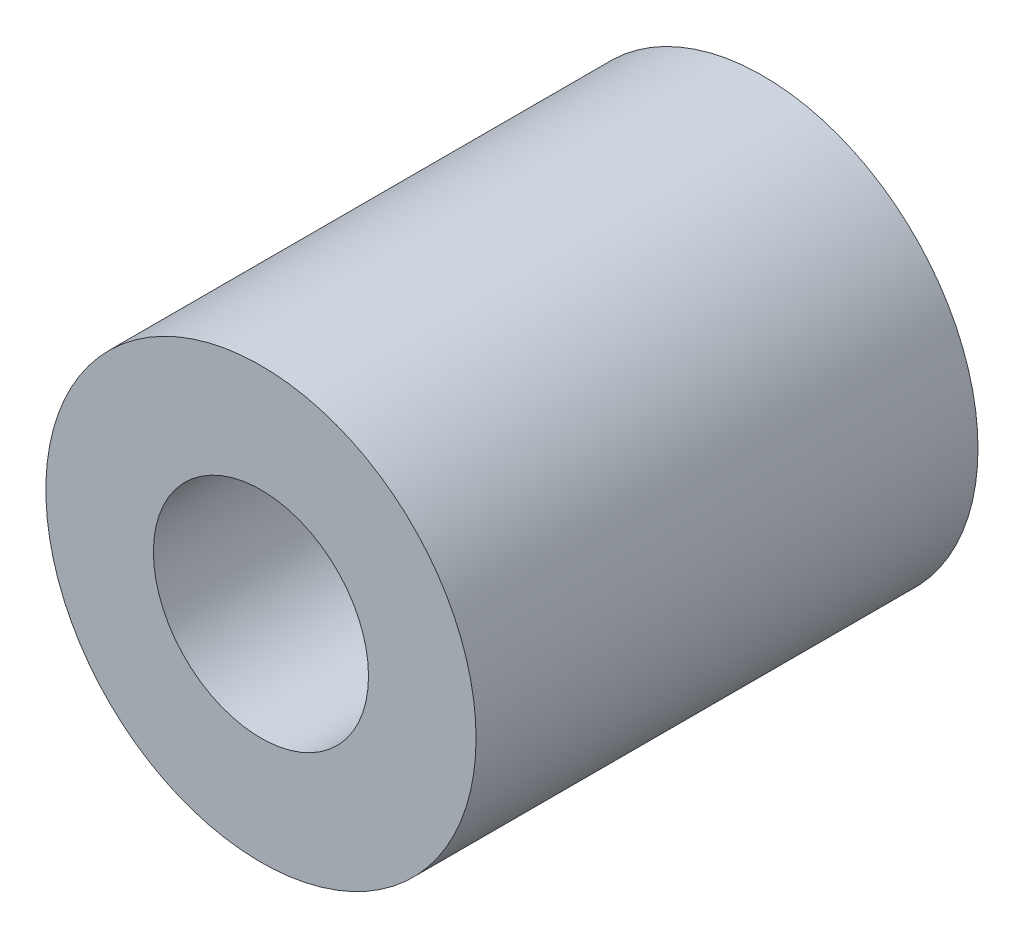
SolidWorks part; units mm, degrees
material "Nylon 101"
ref_plane "Front Plane" through (0, 0, 0) normal (0, 0, 1) x (1, 0, 0)
ref_plane "Top Plane" through (0, 0, 0) normal (0, 1, 0) x (1, 0, 0)
ref_plane "Right Plane" through (0, 0, 0) normal (1, 0, 0) x (0, 0, -1)
sketch "Sketch2" plane through (0, 0, 0) normal (0, 0, 1) x (1, 0, 0)
  circle A0 centre (0, 0) radius 3
  dimension "D1" = 6
extrude "Boss-Extrude1" add sketch "Sketch2" along normal blind 7
sketch "Sketch3" plane through (0, 0, 7) normal (0, 0, 1) x (1, 0, 0)
  circle A0 centre (0, 0) radius 1.5
  dimension "D1" = 3
extrude "Cut-Extrude1" cut sketch "Sketch3" against normal through all
